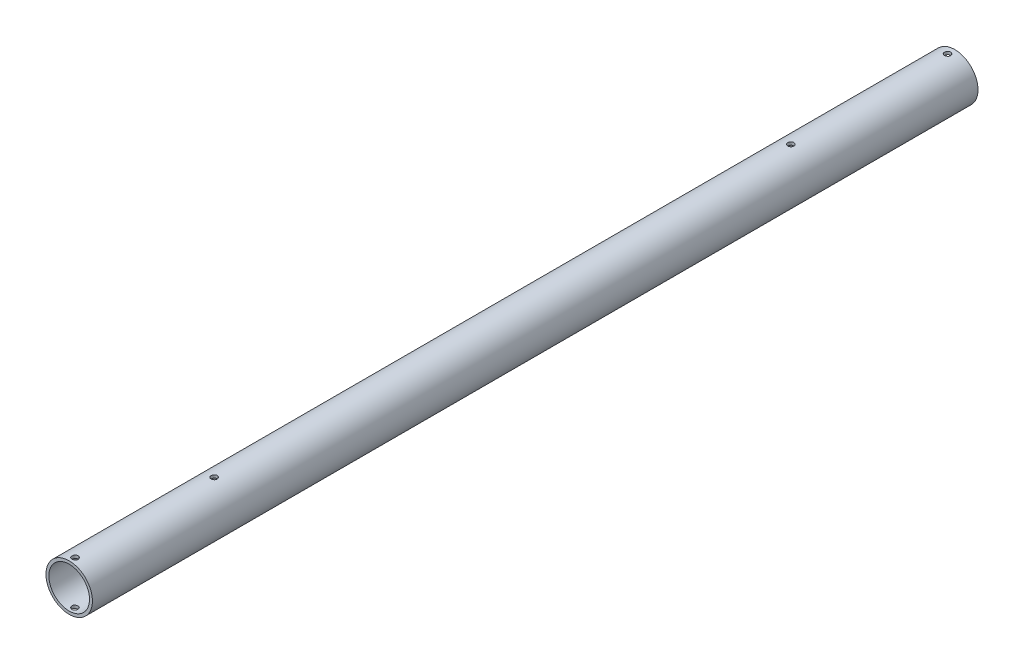
SolidWorks part; units mm, degrees
material "Hexcel AS4C (3000 Filaments)"
ref_plane "Front Plane" through (0, 0, 0) normal (0, 0, 1) x (1, 0, 0)
ref_plane "Top Plane" through (0, 0, 0) normal (0, 1, 0) x (1, 0, 0)
ref_plane "Right Plane" through (0, 0, 0) normal (1, 0, 0) x (0, 0, -1)
sketch "Sketch1" plane through (0, 0, 0) normal (0, 0, 1) x (1, 0, 0)
  circle A0 centre (0, 0) radius 7
  circle A1 centre (0, 0) radius 8
extrude "Boss-Extrude1" add sketch "Sketch1" along normal blind 305
sketch "Sketch2" plane through (0, -10, 0) normal (0, -1, 0) x (1, 0, 0)
  circle A4 centre (0, 2.5) radius 1.05
  circle A5 centre (0, 56.5) radius 1.05
  circle A6 centre (0, 255.1) radius 1.05
  circle A7 centre (0, 303) radius 1.05
extrude "Cut-Extrude2" cut sketch "Sketch2" against normal blind 20
